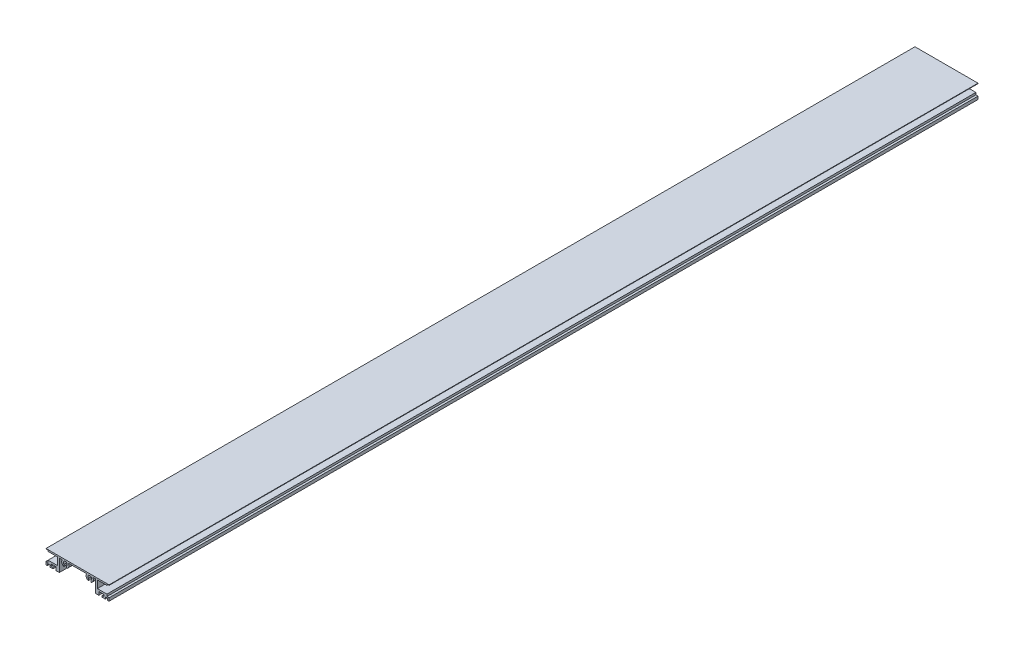
SolidWorks part; units mm, degrees
ref_plane "Piano frontale" through (0, 0, 0) normal (0, 0, 1) x (1, 0, 0)
ref_plane "Piano superiore" through (0, 0, 0) normal (0, 1, 0) x (1, 0, 0)
ref_plane "Piano destro" through (0, 0, 0) normal (1, 0, 0) x (0, 0, -1)
sketch "Schizzo1" plane through (0, 0, 0) normal (0, 0, 1) x (1, 0, 0)
  line L0 (-32.65, 14) -> (-32.65, 8.9)
  line L5 (-32.65, 14) -> (-30.15, 14)
  line L6 (-30.15, 14) -> (-30.15, 10.5)
  line L7 (-32.65, 8.9) -> (-30.45, 8.9)
  line L8 (-30.45, 8.9) -> (-30.45, 7.8)
  line L9 (-30.45, 7.8) -> (-20.55, 7.8)
  line L10 (-20.55, 7.8) -> (-20.55, 0)
  line L11 (-20.55, 0) -> (-30.45, 0)
  line L12 (-30.45, 0) -> (-30.45, -2.2)
  line L13 (-30.45, -2.2) -> (-32.65, -2.2)
  line L14 (-32.65, -2.2) -> (-32.65, -5.3)
  line L15 (-32.65, -5.3) -> (-31.15, -5.3)
  line L16 (-31.15, -5.3) -> (-31.15, -3.3)
  line L17 (-31.15, -3.3) -> (-28.75, -3.3)
  line L18 (-28.75, -3.3) -> (-28.75, -5.3)
  line L19 (-28.75, -5.3) -> (-25.45, -5.3)
  line L20 (-25.45, -5.3) -> (-25.45, -3.8)
  line L21 (-25.45, -3.8) -> (-27.25, -3.8)
  line L22 (-27.25, -3.8) -> (-27.25, -1.8)
  line L23 (-27.25, -1.8) -> (-22.05, -1.8)
  line L24 (-22.05, -1.8) -> (-22.05, -5.3)
  line L25 (-22.05, -5.3) -> (-18.85, -5.3)
  line L26 (-18.85, -5.3) -> (-18.85, 7.8)
  line L27 (-18.85, 7.8) -> (-15.8215, 7.8)
  line L28 (0, 9.4) -> (0, -9.65)
  line L29 (-30.15, 10.5) -> (-29.15, 10.5)
  line L30 (-29.15, 10.5) -> (-29.15, 9.4)
  line L31 (-29.15, 9.4) -> (29.15, 9.4)
  line L32 (11.4, 6.05) -> (-11.4, 6.05) construction
  line L33 (-12.6595, 3.681) -> (-12.5509, 3.8081) construction
  line L35 (-14.0741, 4.4052) -> (-14.0741, 2.5)
  line L37 (-11.2211, 4.4052) -> (-11.2211, 2.5)
  line L38 (-12.7442, 3.8081) -> (-12.6595, 3.681) construction
  line L39 (-14.4234, 2.5) -> (-14.0741, 2.5)
  line L40 (-11.2211, 2.5) -> (-10.8718, 2.5)
  line L41 (-9.4736, 7.8) -> (9.4736, 7.8)
  line L42 (12.7442, 3.8081) -> (12.6595, 3.681) construction
  line L43 (12.6595, 3.681) -> (12.5509, 3.8081) construction
  line L44 (11.2211, 2.5) -> (10.8718, 2.5)
  line L45 (14.4234, 2.5) -> (14.0741, 2.5)
  line L46 (11.2211, 4.4052) -> (11.2211, 2.5)
  line L47 (14.0741, 4.4052) -> (14.0741, 2.5)
  line L48 (29.15, 10.5) -> (29.15, 9.4)
  line L49 (30.15, 10.5) -> (29.15, 10.5)
  line L50 (18.85, 7.8) -> (15.8215, 7.8)
  line L51 (18.85, -5.3) -> (18.85, 7.8)
  line L52 (22.05, -5.3) -> (18.85, -5.3)
  line L53 (22.05, -1.8) -> (22.05, -5.3)
  line L54 (27.25, -1.8) -> (22.05, -1.8)
  line L55 (27.25, -3.8) -> (27.25, -1.8)
  line L56 (25.45, -3.8) -> (27.25, -3.8)
  line L57 (25.45, -5.3) -> (25.45, -3.8)
  line L58 (28.75, -5.3) -> (25.45, -5.3)
  line L59 (28.75, -3.3) -> (28.75, -5.3)
  line L60 (31.15, -3.3) -> (28.75, -3.3)
  line L61 (31.15, -5.3) -> (31.15, -3.3)
  line L62 (32.65, -5.3) -> (31.15, -5.3)
  line L63 (32.65, -2.2) -> (32.65, -5.3)
  line L64 (30.45, -2.2) -> (32.65, -2.2)
  line L65 (30.45, 0) -> (30.45, -2.2)
  line L66 (20.55, 0) -> (30.45, 0)
  line L67 (20.55, 7.8) -> (20.55, 0)
  line L68 (30.45, 7.8) -> (20.55, 7.8)
  line L69 (30.45, 8.9) -> (30.45, 7.8)
  line L70 (32.65, 8.9) -> (30.45, 8.9)
  line L71 (30.15, 14) -> (30.15, 10.5)
  line L72 (32.65, 14) -> (30.15, 14)
  line L73 (32.65, 14) -> (32.65, 8.9)
  arc A0 (-12.7442, 3.8081) -> (-12.5509, 3.8081) centre (-12.6476, 5.8029) ccw
  arc A1 (-15.8215, 7.8) -> (-14.4234, 2.5) centre (-12.6476, 5.8029) ccw
  arc A2 (-10.8718, 2.5) -> (-9.4736, 7.8) centre (-12.6476, 5.8029) ccw
  arc A3 (-11.2211, 4.4052) -> (-14.0741, 4.4052) centre (-12.6476, 5.8029) ccw
  arc A4 (11.2211, 4.4052) -> (14.0741, 4.4052) centre (12.6476, 5.8029) cw
  arc A5 (10.8718, 2.5) -> (9.4736, 7.8) centre (12.6476, 5.8029) cw
  arc A6 (15.8215, 7.8) -> (14.4234, 2.5) centre (12.6476, 5.8029) cw
  arc A7 (12.7442, 3.8081) -> (12.5509, 3.8081) centre (12.6476, 5.8029) cw
  point P0 (0, 0)
  point P6 (-20.45, -5.3)
  point P36 (-12.6595, 3.681)
  point P51 (0, 6.05)
  point P58 (0, 7.8)
  point P86 (12.6595, 3.681)
  dimension "D26" = 7.5
  dimension "D1" = 3.2
  dimension "D2" = 19.3
  dimension "D3" = 13.1
  dimension "D4" = 32.65
  dimension "D5" = 3.4
  dimension "D6" = 3.3
  dimension "D7" = 2.4
  dimension "D8" = 1.5
  dimension "D9" = 2
  dimension "D10" = 5.2
  dimension "D11" = 1.5
  dimension "D12" = 3.5
  dimension "D13" = 19.3
  dimension "D14" = 1.8
  dimension "D15" = 3.1
  dimension "D16" = 2.2
  dimension "D17" = 1.7
  dimension "D18" = 5.1
  dimension "D19" = 13.1
  dimension "D20" = 1.6
  dimension "D21" = 2.5
  dimension "D22" = 3.5
  dimension "D23" = 3.5
  dimension "D24" = 12.65
  dimension "D25" = 1.75
  dimension "D27" = 5.3
extrude "Estrusione-Estrusione1" add sketch "Schizzo1" along normal blind 900 contours A3 L37 L40 A2 L41 L28 L31 L30 L29 L6 L5 L0 L7 L8 L9 L10 L11 L12 L13 L14 L15 L16 L17 L18 L19 L20 L21 L22 L23 L24 L25 L26 L27 A1 L39 L35 | A6 L50 L51 L52 L53 L54 L55 L56 L57 L58 L59 L60 L61 L62 L63 L64 L65 L66 L67 L68 L69 L70 L73 L72 L71 L49 L48 L31 L28 L41 A5 L44 L46 A4 L47 L45
sketch "Schizzo2" plane through (0, 0, 900) normal (0, 0, 1) x (1, 0, 0)
  line L0 (29.15, 9.4) -> (32.65, 9.4)
  line L1 (32.65, 14) -> (32.65, 8.9) construction
  line L2 (32.65, 9.4) -> (32.65, 14)
  line L3 (32.65, 14) -> (29.15, 14)
  line L4 (29.15, 14) -> (29.15, 9.4)
extrude "Taglio-Estrusione1" cut sketch "Schizzo2" against normal through all
mirror "Specchia1" about plane through (0, 0, 0) normal (1, 0, 0) of "Taglio-Estrusione1"
